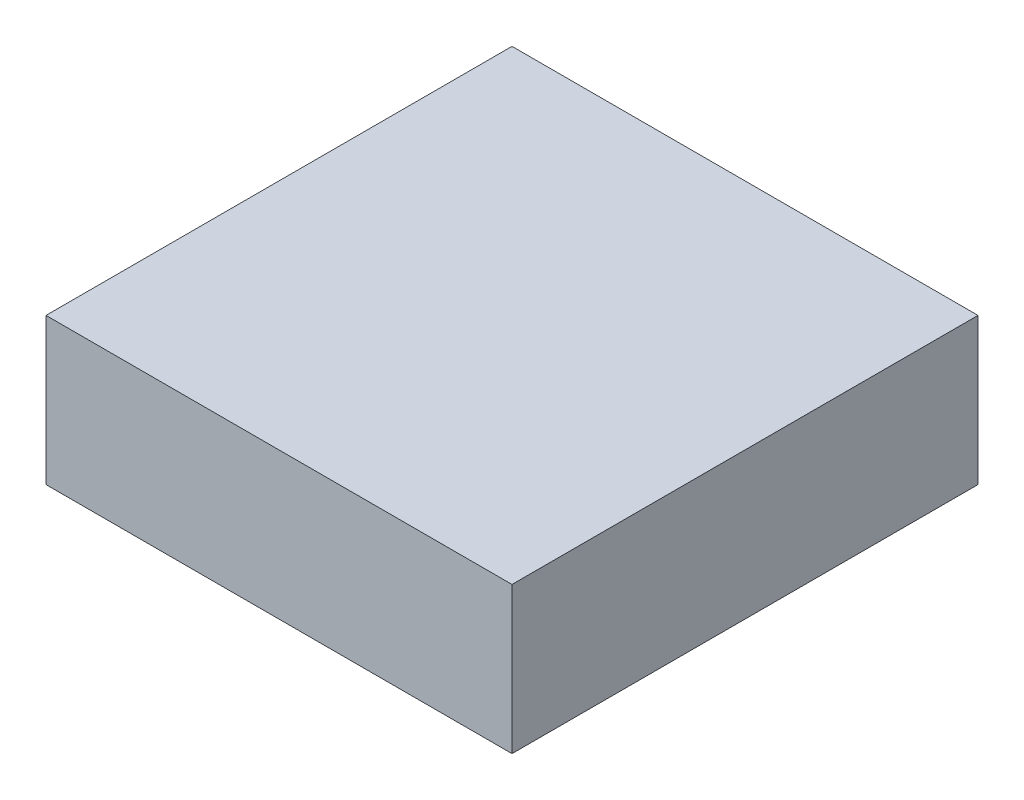
SolidWorks part; units mm, degrees
ref_plane "Front Plane" through (0, 0, 0) normal (0, 0, 1) x (1, 0, 0)
ref_plane "Top Plane" through (0, 0, 0) normal (0, 1, 0) x (1, 0, 0)
ref_plane "Right Plane" through (0, 0, 0) normal (1, 0, 0) x (0, 0, -1)
sketch "Sketch1" plane through (0, 0, 0) normal (0, 1, 0) x (1, 0, 0)
  line L1 (-15.9, -15.9) -> (15.9, -15.9)
  line L2 (-15.9, -15.9) -> (-15.9, 15.9)
  line L3 (-15.9, 15.9) -> (15.9, 15.9)
  line L4 (15.9, -15.9) -> (15.9, 15.9)
  line L5 (-15.9, -15.9) -> (15.9, 15.9) construction
  line L6 (-15.9, 15.9) -> (15.9, -15.9) construction
  point P0 (0, 0)
  dimension "D1" = 31.8
extrude "Boss-Extrude1" add sketch "Sketch1" along normal blind 10
